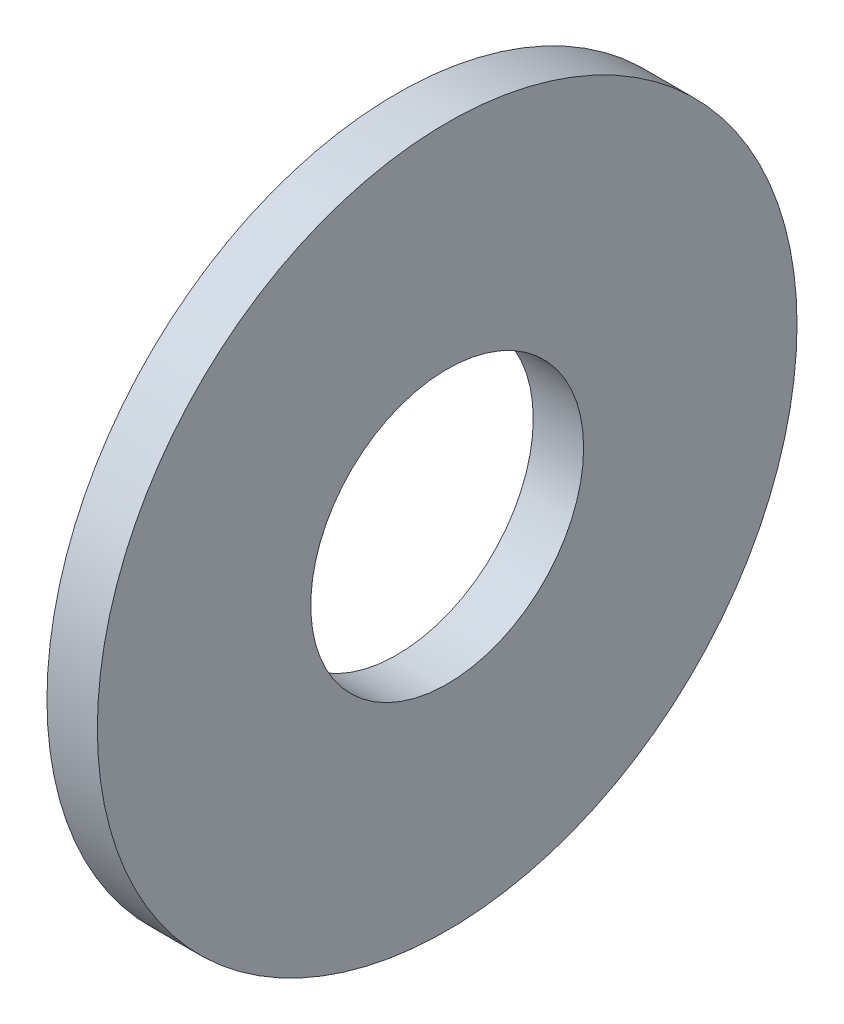
SolidWorks part; units mm, degrees
material "Alloy Steel"
ref_plane "Front Plane" through (0, 0, 0) normal (0, 0, 1) x (1, 0, 0)
ref_plane "Top Plane" through (0, 0, 0) normal (0, 1, 0) x (1, 0, 0)
ref_plane "Right Plane" through (0, 0, 0) normal (1, 0, 0) x (0, 0, -1)
sketch "Sketch1" plane through (0, 0, 0) normal (1, 0, 0) x (0, 0, -1)
  circle A0 centre (0, 0) radius 12.7
  circle A1 centre (0, 0) radius 4.953
  dimension "OD" = 25.4
  dimension "ID" = 9.906
sketch "Sketch2" plane through (0, 0, 0) normal (0, 0, 1) x (1, 0, 0)
  line L0 (-0.9144, 0) -> (0.9144, 0)
  point P4 (0, 0)
  dimension "thickness" = 1.8288
sketch "Sketch3" plane through (0, 0, 0) normal (1, 0, 0) x (0, 0, -1)
  circle A0 centre (0, 0) radius 4.953 construction
  circle A1 centre (0, 0) radius 12.7 construction
  circle A2 centre (0, 0) radius 4.953
  circle A3 centre (0, 0) radius 12.7
extrude "Boss-Extrude1" add sketch "Sketch3" along normal mid plane 1.8288
equation "\"D1@Boss-Extrude1\"=\"thickness@Sketch2\""
